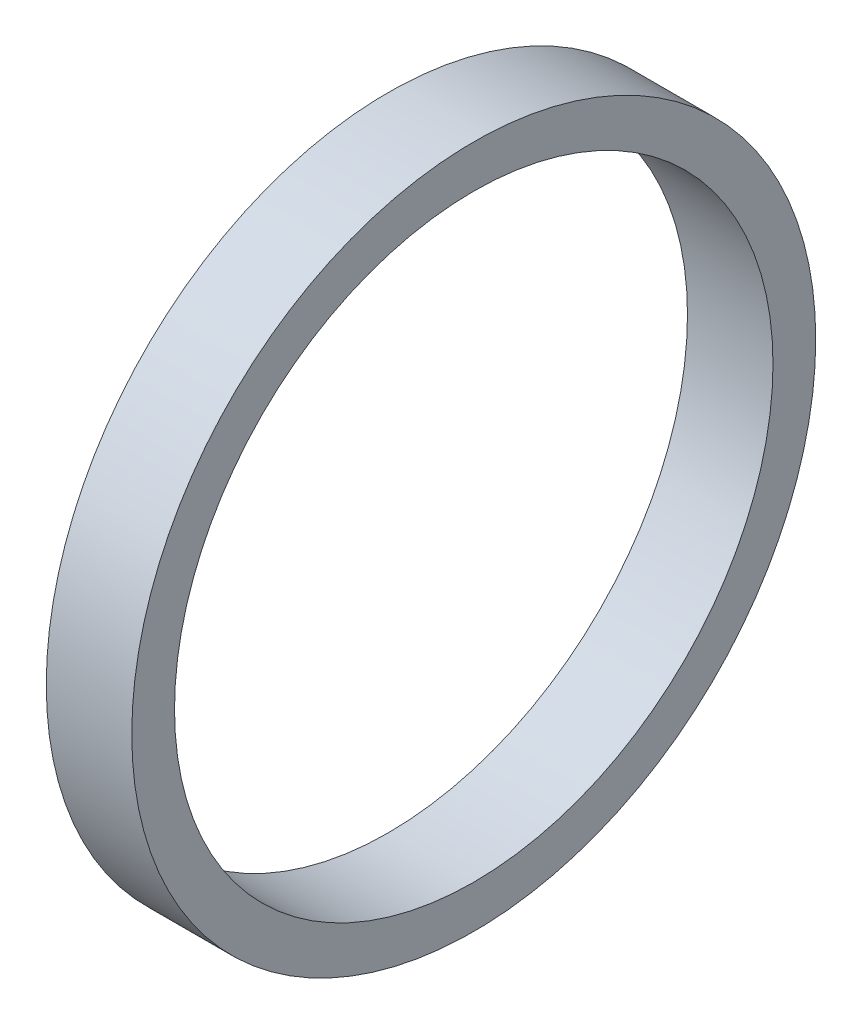
SolidWorks part; units mm, degrees
ref_plane "Front Plane" through (0, 0, 0) normal (0, 0, 1) x (1, 0, 0)
ref_plane "Top Plane" through (0, 0, 0) normal (0, 1, 0) x (1, 0, 0)
ref_plane "Right Plane" through (0, 0, 0) normal (1, 0, 0) x (0, 0, -1)
sketch "Sketch1" plane through (0, 0, 0) normal (0, 0, 1) x (1, 0, 0)
  line L0 (0, 0) -> (10, 0) construction
  line L2 (0, 35) -> (0, 40)
  line L3 (0, 40) -> (10, 40)
  line L4 (10, 40) -> (10, 35)
  line L5 (10, 35) -> (0, 35)
  dimension "D" = 80
  dimension "T" = 5
  dimension "L" = 10
revolve "Revolve1" add sketch "Sketch1" angle 360 about L0
